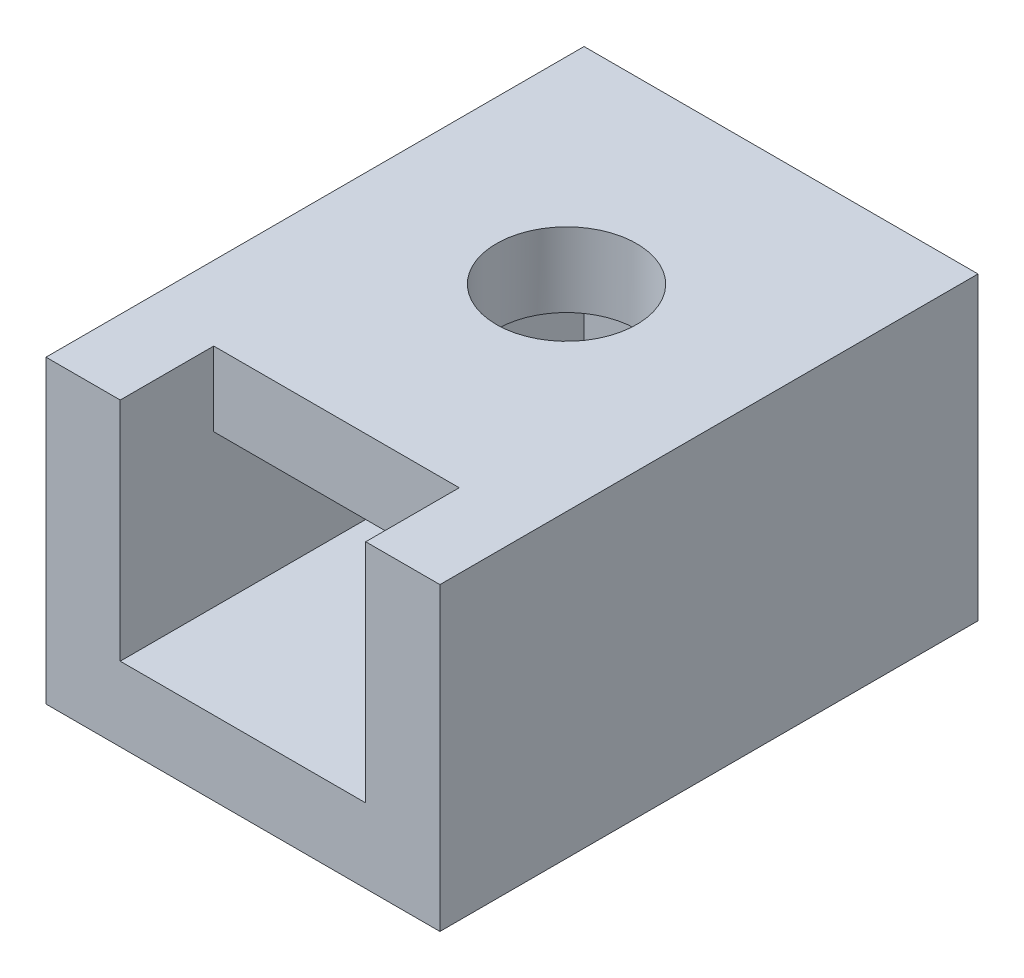
SolidWorks part; units mm, degrees
ref_plane "Front Plane" through (0, 0, 0) normal (0, 0, 1) x (1, 0, 0)
ref_plane "Top Plane" through (0, 0, 0) normal (0, 1, 0) x (1, 0, 0)
ref_plane "Right Plane" through (0, 0, 0) normal (1, 0, 0) x (0, 0, -1)
sketch "Sketch1" plane through (0, 0, 0) normal (0, 0, 1) x (1, 0, 0)
  line L1 (-5.25, -3.25) -> (5.25, -3.25)
  line L2 (-5.25, -3.25) -> (-5.25, 3.25)
  line L3 (-5.25, 3.25) -> (5.25, 3.25)
  line L4 (5.25, -3.25) -> (5.25, 3.25)
  line L5 (-5.25, -3.25) -> (5.25, 3.25) construction
  line L6 (-5.25, 3.25) -> (5.25, -3.25) construction
  point P0 (0, 0)
  dimension "D1" = 6.5
  dimension "D2" = 10.5
extrude "Boss-Extrude1" add sketch "Sketch1" along normal blind 19.84
shell "Shell1" thickness 3.175
sketch "Sketch2" plane through (0, 6.425, 0) normal (0, 1, 0) x (1, 0, 0)
  line L0 (8.425, -19.84) -> (-8.425, -19.84) construction
  line L1 (-5.25, -19.84) -> (5.25, -19.84)
  line L2 (-5.25, -19.84) -> (-5.25, -15.84)
  line L3 (-5.25, -15.84) -> (5.25, -15.84)
  line L4 (5.25, -19.84) -> (5.25, -15.84)
  line L5 (-5.25, -19.84) -> (-5.25, 0) construction
  line L6 (5.25, -19.84) -> (5.25, 0) construction
  circle A0 centre (0, -6) radius 3
  point P12 (1.7764, -6)
  dimension "D2" = 6
  dimension "D1" = 4
  dimension "D3" = 13.84
extrude "Cut-Extrude1" cut sketch "Sketch2" against normal up to next
